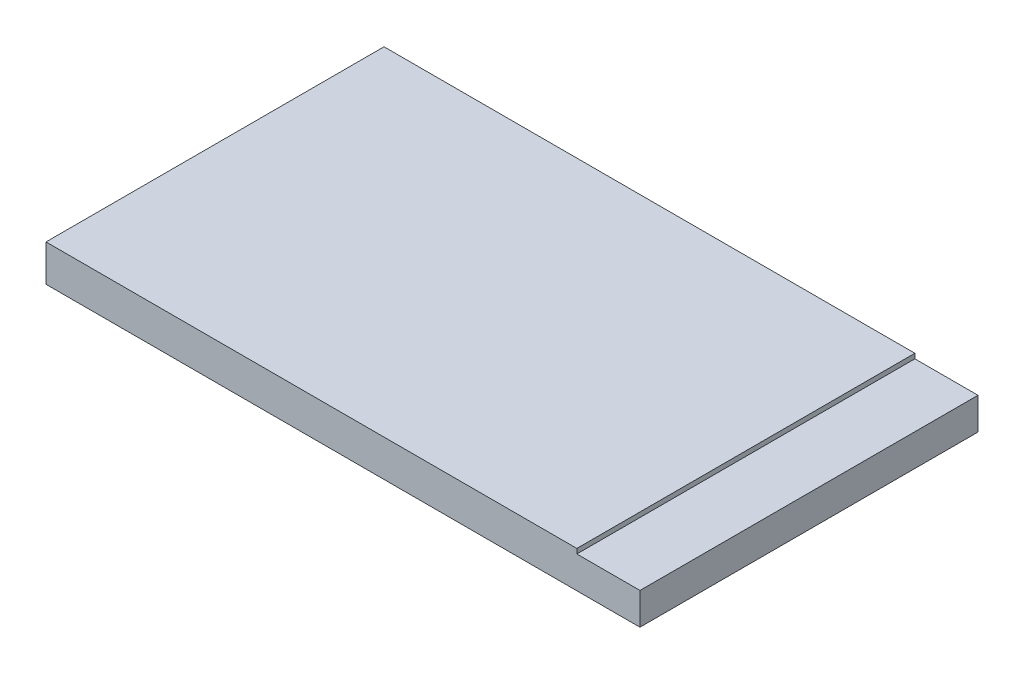
SolidWorks part; units mm, degrees
material "BUTYL"
ref_plane "Front Plane" through (0, 0, 0) normal (0, 0, 1) x (1, 0, 0)
ref_plane "Top Plane" through (0, 0, 0) normal (0, 1, 0) x (1, 0, 0)
ref_plane "Right Plane" through (0, 0, 0) normal (1, 0, 0) x (0, 0, -1)
sketch "Sketch1" plane through (0, 0, 0) normal (0, 1, 0) x (1, 0, 0)
  line L1 (15.621, -8.89) -> (-15.621, -8.89)
  line L2 (15.621, -8.89) -> (15.621, 8.89)
  line L3 (15.621, 8.89) -> (-15.621, 8.89)
  line L4 (-15.621, -8.89) -> (-15.621, 8.89)
  line L5 (15.621, -8.89) -> (-15.621, 8.89) construction
  line L6 (15.621, 8.89) -> (-15.621, -8.89) construction
  point P0 (0, 0)
extrude "Boss-Extrude1" add sketch "Sketch1" along normal blind 1.6764
sketch "Sketch2" plane through (0, 1.6764, 0) normal (0, 1, 0) x (1, 0, 0)
  line L0 (15.621, 8.89) -> (-15.621, 8.89) construction
  line L1 (-15.621, -8.89) -> (12.3007, -8.89)
  line L2 (-15.621, -8.89) -> (-15.621, 8.89)
  line L3 (-15.621, 8.89) -> (12.3007, 8.89)
  line L4 (12.3007, -8.89) -> (12.3007, 8.89)
extrude "Boss-Extrude2" add sketch "Sketch2" along normal blind 0.254
sketch "Sketch3" plane through (0, 1.9304, 0) normal (0, 1, 0) x (1, 0, 0)
  line L0 (12.3007, 0) -> (-1.6947, 0) construction
  line L2 (12.3007, -8.89) -> (12.3007, 8.89) construction
  line L4 (-1.6947, 0) -> (-1.6947, 8.89) construction
  point P6 (0, 0)
  dimension "D1" = 13.9954
